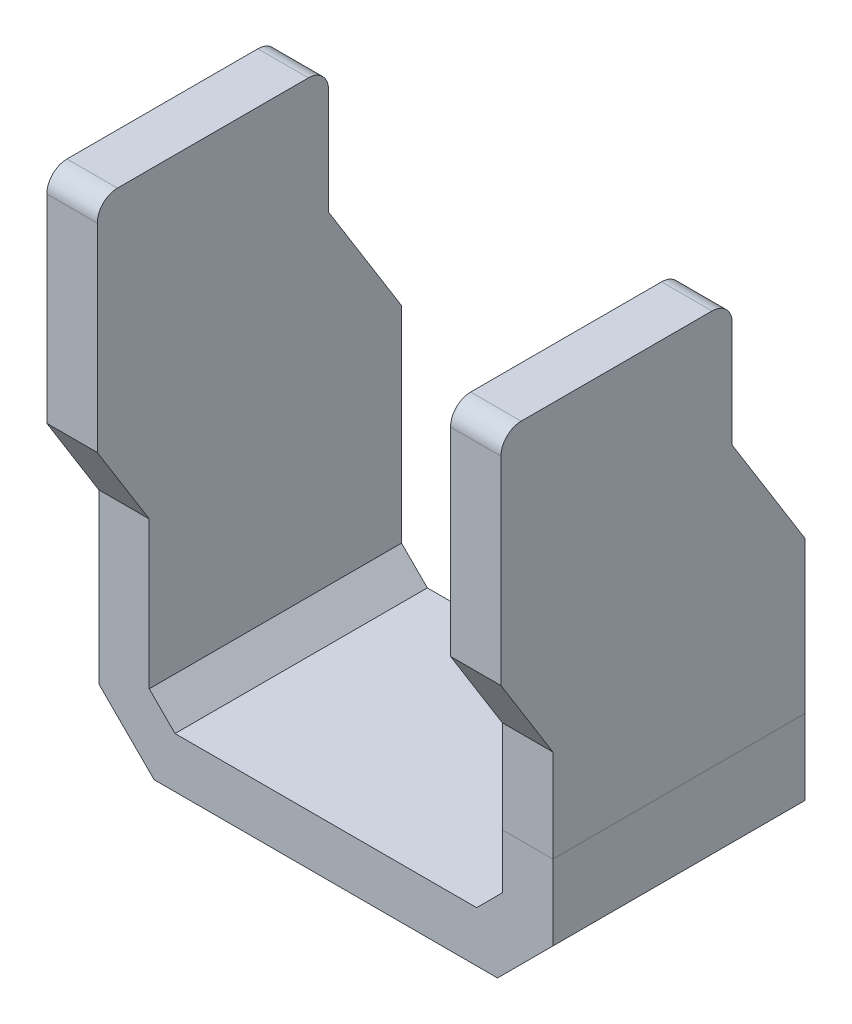
SolidWorks part; units mm, degrees
ref_plane "Front Plane" through (0, 0, 0) normal (0, 0, 1) x (1, 0, 0)
ref_plane "Top Plane" through (0, 0, 0) normal (0, 1, 0) x (1, 0, 0)
ref_plane "Right Plane" through (0, 0, 0) normal (1, 0, 0) x (0, 0, -1)
sketch "Sketch1" plane through (0, 0, 0) normal (0, 0, 1) x (1, 0, 0)
  line L0 (-17.5, 7.9496) -> (-17.5, 2.5593)
  line L1 (-17.5, 2.5593) -> (-14.9407, 0)
  line L2 (-14.9407, 0) -> (0, 0)
  line L3 (-22.5, 7.9496) -> (-22.5, 0.4882)
  line L4 (-22.5, 0.4882) -> (-17.0118, -5)
  line L5 (-17.0118, -5) -> (0, -5)
  line L6 (-22.5, 7.9496) -> (-17.5, 7.9496)
  line L7 (0, 0) -> (0, -5) construction
  line L8 (22.5, 7.9496) -> (17.5, 7.9496)
  line L9 (17.0118, -5) -> (0, -5)
  line L10 (22.5, 0.4882) -> (17.0118, -5)
  line L11 (22.5, 7.9496) -> (22.5, 0.4882)
  line L12 (14.9407, 0) -> (0, 0)
  line L13 (17.5, 2.5593) -> (14.9407, 0)
  line L14 (17.5, 7.9496) -> (17.5, 2.5593)
  point P4 (-45, -5)
  dimension "D2" = 35
  dimension "D4" = 135
extrude "Boss-Extrude1" add sketch "Sketch1" along normal blind 25
sketch "Sketch3" plane through (22.5, 0, 0) normal (1, 0, 0) x (0, 0, -1)
  line L17 (-25, 7.9496) -> (0, 7.9496)
  line L18 (0, 7.9496) -> (0, 22.9496)
  line L21 (-9.2308, 47.0994) -> (-28.1486, 47.0994)
  line L25 (-30.1486, 45.0994) -> (-30.1486, 25.4162)
  line L26 (-7.2308, 45.0994) -> (-7.2308, 34.5775)
  line L27 (-7.2308, 34.5775) -> (0, 22.9496)
  line L28 (-30.1486, 25.4162) -> (-25, 17.1367)
  line L29 (-25, 17.1367) -> (-25, 7.9496)
  arc A4 (-7.2308, 45.0994) -> (-9.2308, 47.0994) centre (-9.2308, 45.0994) ccw
  arc A5 (-28.1486, 47.0994) -> (-30.1486, 45.0994) centre (-28.1486, 45.0994) ccw
  point P4 (-43.2301, 28.7378)
  point P8 (-44.234, 34.8617)
  point P9 (-30, 12.6509)
  point P10 (-36.8567, 25.4489)
  point P11 (-15.4974, 36.3933)
  point P12 (-30, 13.7983)
  point P13 (0, 0)
  point P14 (-14.703, 29.5089)
  point P16 (-11.1725, 29.9502)
  point P17 (-34.2089, 21.3006)
  point P18 (-30, 12.9157)
  point P19 (-37.1215, 22.6245)
  point P20 (-32.0906, 42.0421)
  point P21 (-30, 11.8565)
  point P26 (-9.2308, 37.3642)
  point P27 (-28.8249, 37.0994)
  point P28 (-30.1486, 29.7532)
  point P29 (-25, 17.1367)
  dimension "D1" = 2
  dimension "D2" = 15
  dimension "D3" = 10.5219
extrude "Boss-Extrude3" add sketch "Sketch3" against normal up to surface (5 mm away) separate body up to face at (17.5, 5.2544, 12.5)
fillet "Fillet1" [suppressed] radius 5
ref_plane "Plane2" through (0, 0, 0) normal (-1, 0, 0) x (0, 0, 1)
mirror "Mirror3" [suppressed] about plane through (0, 0, 0) normal (-1, 0, 0)
mirror "Mirror5" about plane through (0, 0, 0) normal (-1, 0, 0) of "Boss-Extrude3"
sketch "Sketch4" [suppressed] plane through (45, 0, 0) normal (1, 0, 0) x (0, 0, -1)
  line L60 (-18.5197, 54.3817) -> (-43.576, 54.3817)
  line L61 (-18.794, 54.3817) -> (-35, 54.3817)
  line L83 (-15.642, 24.553) -> (-16.7044, 50.2548)
  line L84 (-3, 6.9825) -> (-15.642, 24.553)
  line L85 (-3, 5.5211) -> (-3, 6.9825)
  line L86 (-37, 50.3787) -> (-37, 7.9496)
  line L87 (-37, 7.9496) -> (-37, 5.5211)
  line L88 (-37, 5.5211) -> (-3, 5.5211)
  line L89 (-15.642, 24.553) -> (-16.7957, 52.4643)
  line L90 (-3, 6.9825) -> (-15.642, 24.553)
  line L91 (-3, 5.5211) -> (-3, 6.9825)
  line L92 (-37, 52.3817) -> (-37, 7.9496)
  line L93 (-37, 7.9496) -> (-37, 5.5211)
  line L94 (-37, 5.5211) -> (-3, 5.5211)
  arc A7 (-16.7957, 52.4643) -> (-18.794, 54.3817) centre (-18.794, 52.3817) ccw
  arc A8 (-37, 52.3817) -> (-35, 54.3817) centre (-35, 52.3817) cw
  point P0 (-23.6064, 48.2996)
  dimension "D3" = 2
  dimension "D1" = 3
  dimension "D2" = 9
extrude "Cut-Extrude1" [suppressed] cut sketch "Sketch4" against normal through all
